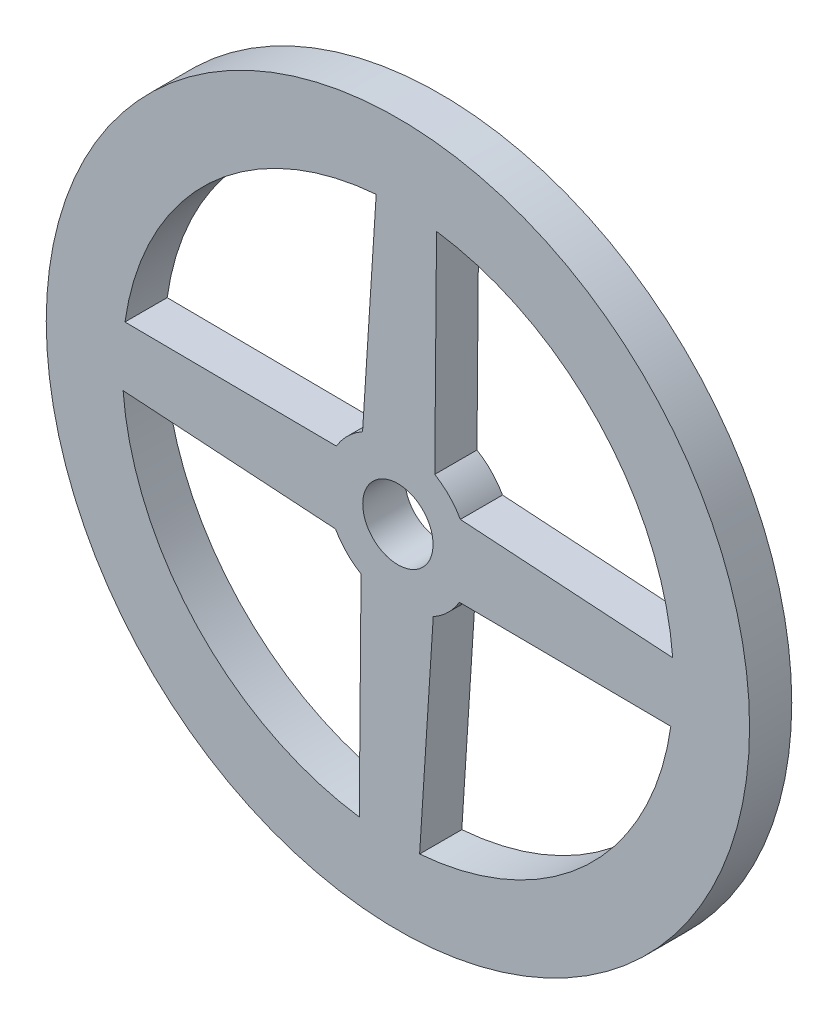
SolidWorks part; units mm, degrees
ref_plane "Front Plane" through (0, 0, 0) normal (0, 0, 1) x (1, 0, 0)
ref_plane "Top Plane" through (0, 0, 0) normal (0, 1, 0) x (1, 0, 0)
ref_plane "Right Plane" through (0, 0, 0) normal (1, 0, 0) x (0, 0, -1)
sketch "Sketch1" plane through (0, 0, 0) normal (0, 0, 1) x (1, 0, 0)
  line L0 (2.7459, 19.402) -> (2.6205, 4.376)
  line L1 (4.4389, 2.5125) -> (19.5345, 1.5433)
  line L2 (2.5125, -4.4389) -> (1.5433, -19.5345)
  line L3 (19.402, -2.7459) -> (4.376, -2.6205)
  line L4 (-4.4389, -2.5125) -> (-19.5345, -1.5433)
  line L5 (-2.7459, -19.402) -> (-2.6205, -4.376)
  line L6 (-2.5125, 4.4389) -> (-1.5433, 19.5345)
  line L7 (-19.402, 2.7459) -> (-4.376, 2.6205)
  circle A0 centre (0, 0) radius 25
  arc A1 (2.6205, 4.376) -> (4.4389, 2.5125) centre (0, 0) cw
  arc A2 (2.7459, 19.402) -> (19.5345, 1.5433) centre (0, 0) cw
  arc A3 (19.402, -2.7459) -> (1.5433, -19.5345) centre (0, 0) cw
  arc A4 (4.376, -2.6205) -> (2.5125, -4.4389) centre (0, 0) cw
  arc A5 (-2.7459, -19.402) -> (-19.5345, -1.5433) centre (0, 0) cw
  arc A6 (-2.6205, -4.376) -> (-4.4389, -2.5125) centre (0, 0) cw
  arc A7 (-19.402, 2.7459) -> (-1.5433, 19.5345) centre (0, 0) cw
  arc A8 (-4.376, 2.6205) -> (-2.5125, 4.4389) centre (0, 0) cw
  point P24 (0, 0)
  dimension "D1" = 50
  dimension "D2" = 4
extrude "Boss-Extrude1" add sketch "Sketch1" along normal blind 3
sketch "Sketch2" plane through (0, 0, 0) normal (0, 0, -1) x (-1, 0, 0)
  circle A0 centre (0, 0) radius 2.5
  dimension "D1" = 5
extrude "Cut-Extrude1" cut sketch "Sketch2" against normal through all both
